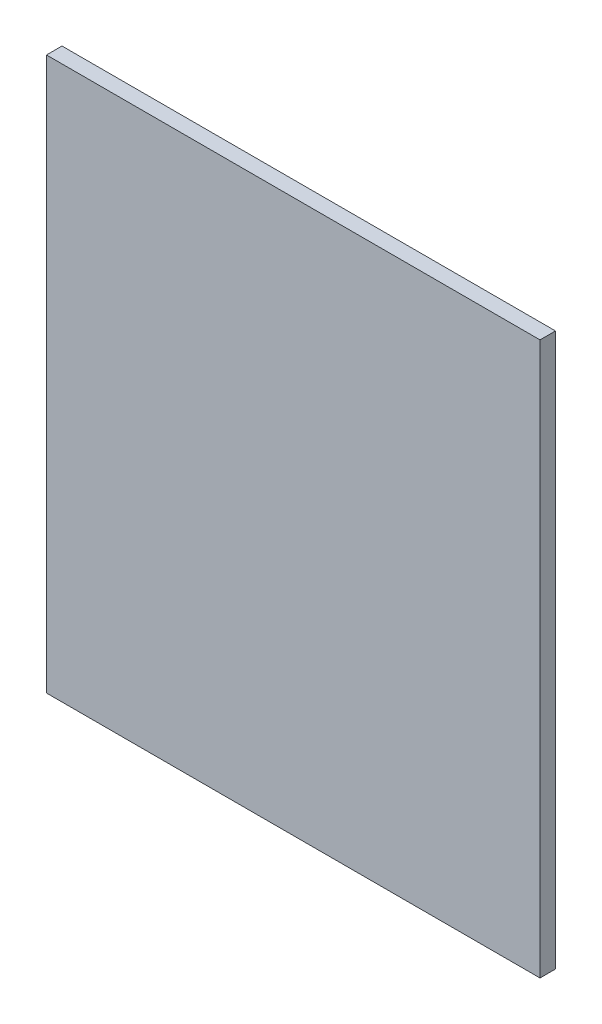
SolidWorks part; units mm, degrees
material "Beech"
ref_plane "Front Plane" through (0, 0, 0) normal (0, 0, 1) x (1, 0, 0)
ref_plane "Top Plane" through (0, 0, 0) normal (0, 1, 0) x (1, 0, 0)
ref_plane "Right Plane" through (0, 0, 0) normal (1, 0, 0) x (0, 0, -1)
sketch "Sketch1" plane through (0, 0, 0) normal (0, 0, 1) x (1, 0, 0)
  line L0 (-44.076, 395.8385) -> (-44.076, -31.9615)
  line L1 (-44.076, -31.9615) -> (337.964, -31.9615)
  line L2 (337.964, -31.9615) -> (337.964, 395.8385)
  line L3 (337.964, 395.8385) -> (-44.076, 395.8385)
extrude "Boss-Extrude1" add sketch "Sketch1" along normal blind 12
